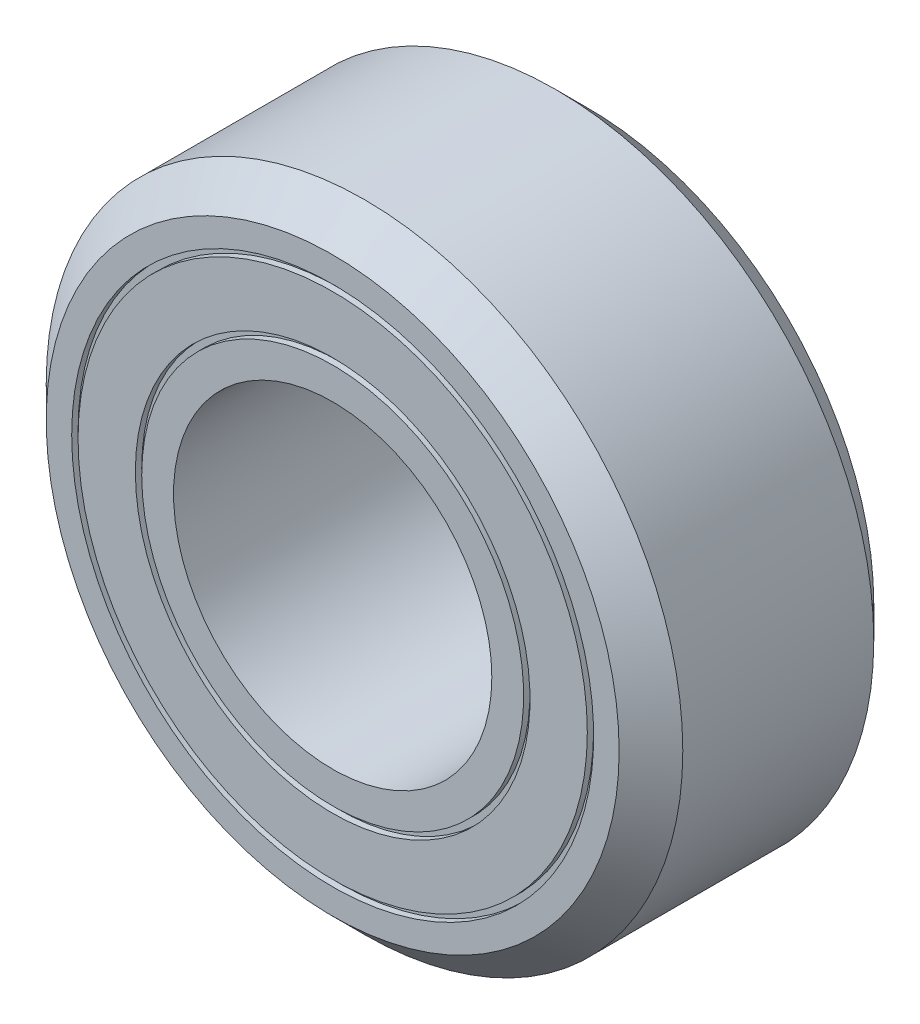
SolidWorks part; units mm, degrees
ref_plane "Płaszczyzna przednia" through (0, 0, 0) normal (0, 0, 1) x (1, 0, 0)
ref_plane "Płaszczyzna górna" through (0, 0, 0) normal (0, 1, 0) x (1, 0, 0)
ref_plane "Płaszczyzna prawa" through (0, 0, 0) normal (1, 0, 0) x (0, 0, -1)
sketch "Sketch1" plane through (0, 0, 0) normal (0, 0, 1) x (1, 0, 0)
  circle A0 centre (0, 0) radius 5
  circle A1 centre (0, 0) radius 2.5
  dimension "D1" = 10
  dimension "D2" = 5
extrude "Boss-Extrude1" add sketch "Sketch1" along normal blind 4
chamfer "Chamfer1" distance 0.5 2 edges at (5, 0, 0) (5, 0, 4)
ref_plane "Plane1" through (0, 0, 2) normal (0, 0, -1) x (-1, 0, 0)
sketch "Sketch2" plane through (0, 0, 0) normal (0, 0, -1) x (-1, 0, 0)
  circle A0 centre (0, 0) radius 3.5 construction
  circle A1 centre (0, 0) radius 4
  circle A2 centre (0, 0) radius 3
  circle A3 centre (0, 0) radius 4.1
  circle A4 centre (0, 0) radius 3.1
  circle A5 centre (0, 0) radius 3.9
  circle A6 centre (0, 0) radius 2.9
  dimension "D1" = 7
  dimension "D4" = 0.1
  dimension "D2" = 0.5
  dimension "D3" = 0.5
  dimension "D5" = 0.1
extrude "Cut-Extrude1" cut sketch "Sketch2" against normal blind 0.1 contours A3 A1 | A2 | A4
mirror "Mirror1" about plane through (0, 0, 2) normal (0, 0, -1) of "Cut-Extrude1"
